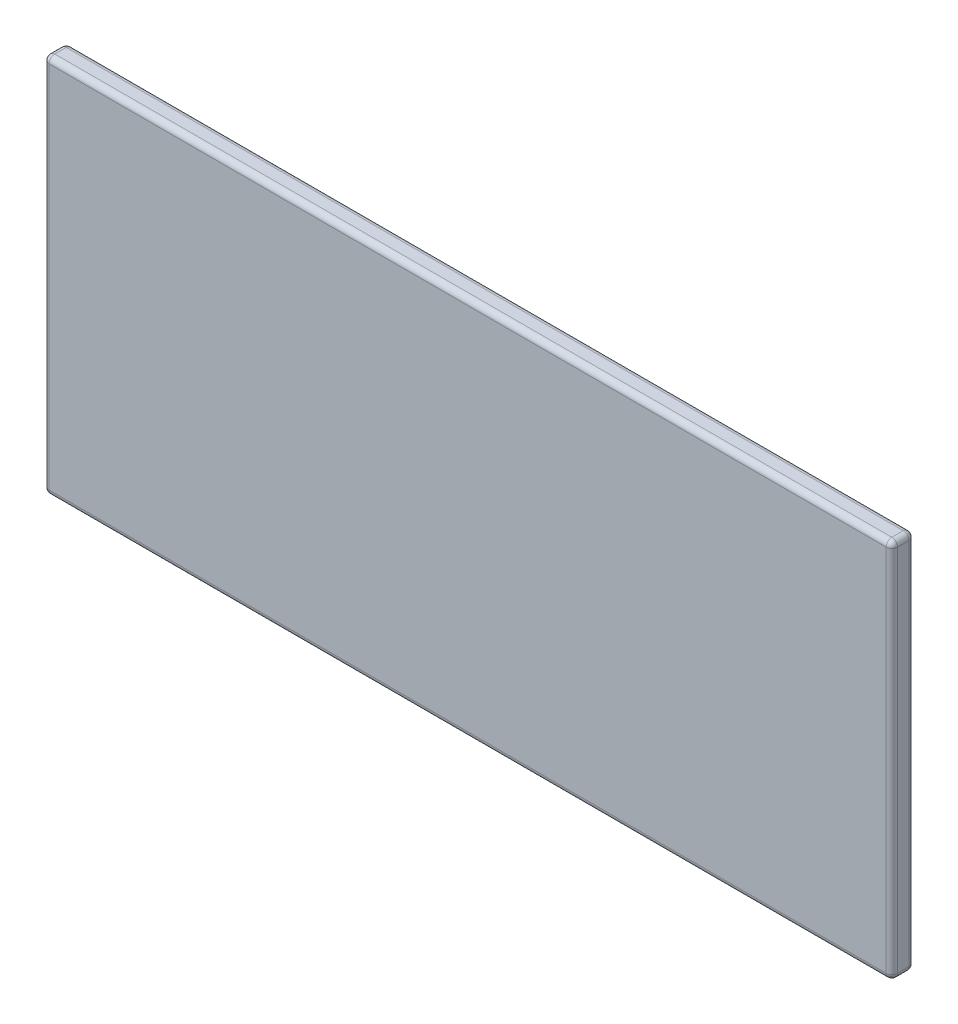
SolidWorks part; units mm, degrees
ref_plane "Front Plane" through (0, 0, 0) normal (0, 0, 1) x (1, 0, 0)
ref_plane "Top Plane" through (0, 0, 0) normal (0, 1, 0) x (1, 0, 0)
ref_plane "Right Plane" through (0, 0, 0) normal (1, 0, 0) x (0, 0, -1)
sketch "Sketch1" plane through (0, 0, 0) normal (0, 0, 1) x (1, 0, 0)
  line L1 (-37.35, -16.75) -> (37.35, -16.75)
  line L2 (-37.35, -16.75) -> (-37.35, 16.75)
  line L3 (-37.35, 16.75) -> (37.35, 16.75)
  line L4 (37.35, -16.75) -> (37.35, 16.75)
  line L5 (-37.35, -16.75) -> (37.35, 16.75) construction
  line L6 (-37.35, 16.75) -> (37.35, -16.75) construction
  point P0 (0, 0)
  dimension "D1" = 74.7
  dimension "D2" = 33.5
extrude "Boss-Extrude1" add sketch "Sketch1" along normal blind 2
fillet "Fillet1" radius 0.5 12 edges at (0, -16.75, 2) (0, -16.75, 0) (-37.35, 0, 2) (-37.35, -16.75, 1) (-37.35, 0, 0) (0, 16.75, 2) (-37.35, 16.75, 1) (0, 16.75, 0) (37.35, -16.75, 1) (37.35, 0, 2) (37.35, 16.75, 1) (37.35, 0, 0)
